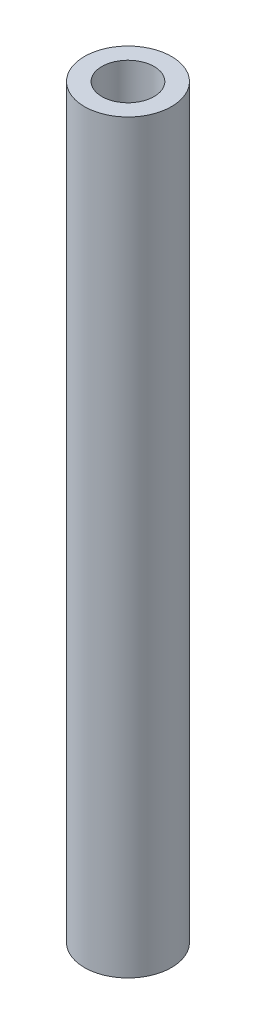
SolidWorks part; units mm, degrees
material "6061 合金"
ref_plane "前视基准面" through (0, 0, 0) normal (0, 0, 1) x (1, 0, 0)
ref_plane "上视基准面" through (0, 0, 0) normal (0, 1, 0) x (1, 0, 0)
ref_plane "右视基准面" through (0, 0, 0) normal (1, 0, 0) x (0, 0, -1)
other "Configuration Table"
sketch "草图1" plane through (0, 0, 0) normal (0, 1, 0) x (1, 0, 0)
  circle A0 centre (0, 0) radius 3.5
  circle A1 centre (0, 0) radius 2.1
  dimension "D1" = 7
  dimension "D2" = 4.2
extrude "凸台-拉伸1" add sketch "草图1" along normal blind 60
